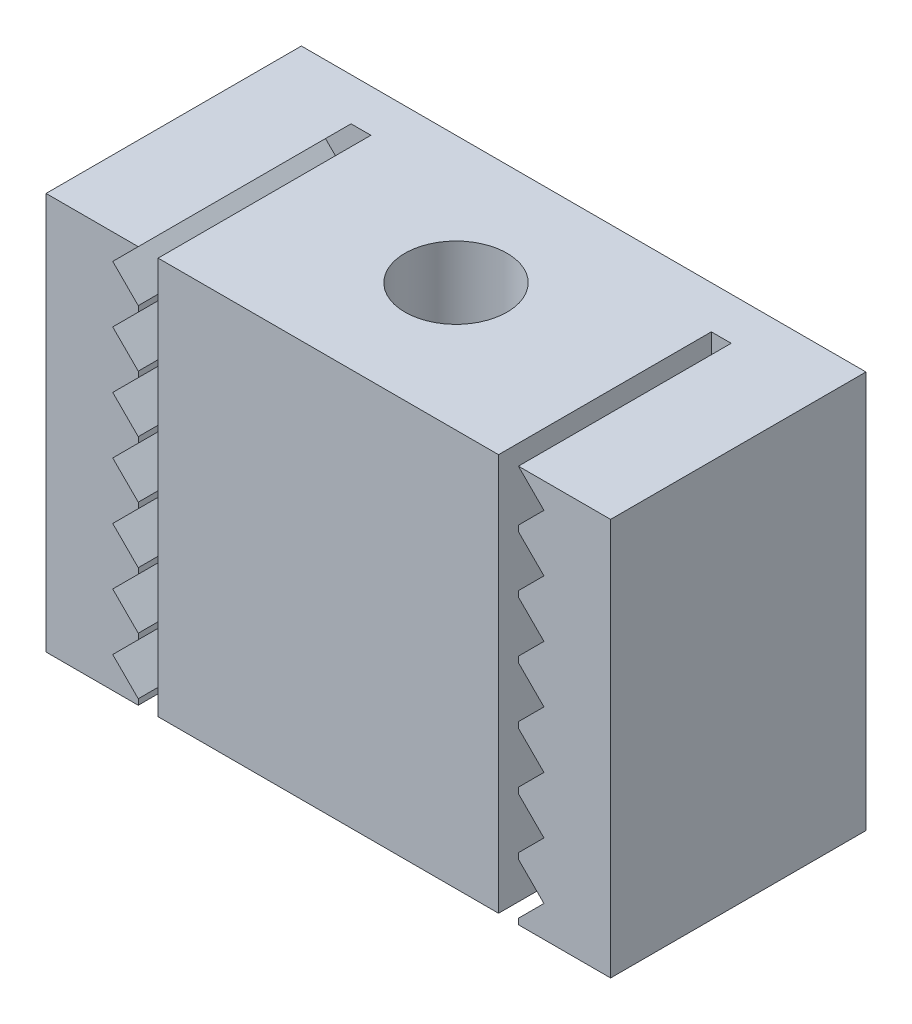
SolidWorks part; units mm, degrees
ref_plane "Front Plane" through (0, 0, 0) normal (0, 0, 1) x (1, 0, 0)
ref_plane "Top Plane" through (0, 0, 0) normal (0, 1, 0) x (1, 0, 0)
ref_plane "Right Plane" through (0, 0, 0) normal (1, 0, 0) x (0, 0, -1)
sketch "Sketch1" plane through (0, 0, 0) normal (0, 0, 1) x (1, 0, 0)
  line L0 (0, 0) -> (0, 16.9576) construction
  line L1 (-9.95, 0) -> (9.95, 0)
  line L2 (9.95, 0) -> (9.95, 14)
  line L3 (9.95, 14) -> (-9.95, 14)
  line L4 (-9.95, 0) -> (-9.95, 14)
  point P8 (0, 14)
  dimension "D1" = 19.9
  dimension "D2" = 14
extrude "Boss-Extrude1" add sketch "Sketch1" along normal blind 9
sketch "Sketch2" plane through (0, 14, 0) normal (0, 1, 0) x (1, 0, 0)
  line L0 (0, 0) -> (0, -9) construction
  line L1 (9.95, -9) -> (-9.95, -9) construction
  circle A0 centre (0, -4.5) radius 1.8
  dimension "D1" = 3.6
extrude "Cut-Extrude1" cut sketch "Sketch2" against normal through all
sketch "Sketch3" plane through (0, 0, 9) normal (0, 0, 1) x (1, 0, 0)
  line L0 (0, 0) -> (0, 14) construction
  line L1 (-9.95, 0) -> (9.95, 0) construction
  line L2 (9.95, 14) -> (-9.95, 14) construction
  line L3 (6, 14) -> (6, 0)
  line L4 (6.7, 12.2) -> (6.7, 12)
  line L5 (6.7, 14) -> (7.6, 13.1)
  line L6 (7.6, 13.1) -> (6.7, 13.1) construction
  line L7 (6.7, 12.2) -> (7.6, 13.1)
  line L8 (6.7, 12) -> (7.6, 11.1)
  line L9 (6.7, 10.2) -> (7.6, 11.1)
  line L10 (6.7, 10) -> (7.6, 9.1)
  line L11 (6.7, 8.2) -> (7.6, 9.1)
  line L12 (6.7, 8) -> (7.6, 7.1)
  line L13 (6.7, 6.2) -> (7.6, 7.1)
  line L14 (6.7, 6) -> (7.6, 5.1)
  line L15 (6.7, 4.2) -> (7.6, 5.1)
  line L16 (6.7, 4) -> (7.6, 3.1)
  line L17 (6.7, 2.2) -> (7.6, 3.1)
  line L18 (6.7, 2) -> (7.6, 1.1)
  line L19 (6.7, 0.2) -> (7.6, 1.1)
  line L20 (6, 14) -> (6.7, 14)
  line L21 (6, 0) -> (6.7, 0)
  line L22 (6.7, 14) -> (6.7, 13.1) construction
  line L23 (6.7, 13.1) -> (6.7, 12.2) construction
  line L24 (6.7, 12) -> (6.7, 10.2) construction
  line L25 (6.7, 10.2) -> (6.7, 10)
  line L26 (6.7, 10) -> (6.7, 8.2) construction
  line L27 (6.7, 8.2) -> (6.7, 8)
  line L28 (6.7, 8) -> (6.7, 6.2) construction
  line L29 (6.7, 6.2) -> (6.7, 6)
  line L30 (6.7, 6) -> (6.7, 4.2) construction
  line L31 (6.7, 4.2) -> (6.7, 4)
  line L32 (6.7, 4) -> (6.7, 2.2) construction
  line L33 (6.7, 2.2) -> (6.7, 2)
  line L34 (6.7, 2) -> (6.7, 0.2) construction
  line L35 (6.7, 0.2) -> (6.7, 0)
  line L36 (-6.7, 2) -> (-6.7, 0.2) construction
  line L37 (-6.7, 4) -> (-6.7, 2.2) construction
  line L38 (-6.7, 6) -> (-6.7, 4.2) construction
  line L39 (-6.7, 8) -> (-6.7, 6.2) construction
  line L40 (-6.7, 10) -> (-6.7, 8.2) construction
  line L41 (-6.7, 12) -> (-6.7, 10.2) construction
  line L42 (-6.7, 13.1) -> (-6.7, 12.2) construction
  line L43 (-6.7, 14) -> (-6.7, 13.1) construction
  line L44 (-7.6, 13.1) -> (-6.7, 13.1) construction
  line L45 (-6.7, 0.2) -> (-6.7, 0)
  line L46 (-6.7, 2.2) -> (-6.7, 2)
  line L47 (-6.7, 4.2) -> (-6.7, 4)
  line L48 (-6.7, 6.2) -> (-6.7, 6)
  line L49 (-6.7, 8.2) -> (-6.7, 8)
  line L50 (-6.7, 10.2) -> (-6.7, 10)
  line L51 (-6, 0) -> (-6.7, 0)
  line L52 (-6, 14) -> (-6.7, 14)
  line L53 (-6.7, 0.2) -> (-7.6, 1.1)
  line L54 (-6.7, 2) -> (-7.6, 1.1)
  line L55 (-6.7, 2.2) -> (-7.6, 3.1)
  line L56 (-6.7, 4) -> (-7.6, 3.1)
  line L57 (-6.7, 4.2) -> (-7.6, 5.1)
  line L58 (-6.7, 6) -> (-7.6, 5.1)
  line L59 (-6.7, 6.2) -> (-7.6, 7.1)
  line L60 (-6.7, 8) -> (-7.6, 7.1)
  line L61 (-6.7, 8.2) -> (-7.6, 9.1)
  line L62 (-6.7, 10) -> (-7.6, 9.1)
  line L63 (-6.7, 10.2) -> (-7.6, 11.1)
  line L64 (-6.7, 12) -> (-7.6, 11.1)
  line L65 (-6.7, 12.2) -> (-7.6, 13.1)
  line L66 (-6.7, 14) -> (-7.6, 13.1)
  line L67 (-6.7, 12.2) -> (-6.7, 12)
  line L68 (-6, 14) -> (-6, 0)
  dimension "D1" = 0.7
  dimension "D2" = 1.6
  dimension "D3" = 90
  dimension "D4" = 6
  dimension "D6" = 2
  dimension "D5" = 7
extrude "Cut-Extrude2" cut sketch "Sketch3" against normal offset from surface (7.5 mm away) 1.5 up to face at (0, 7, 0)
